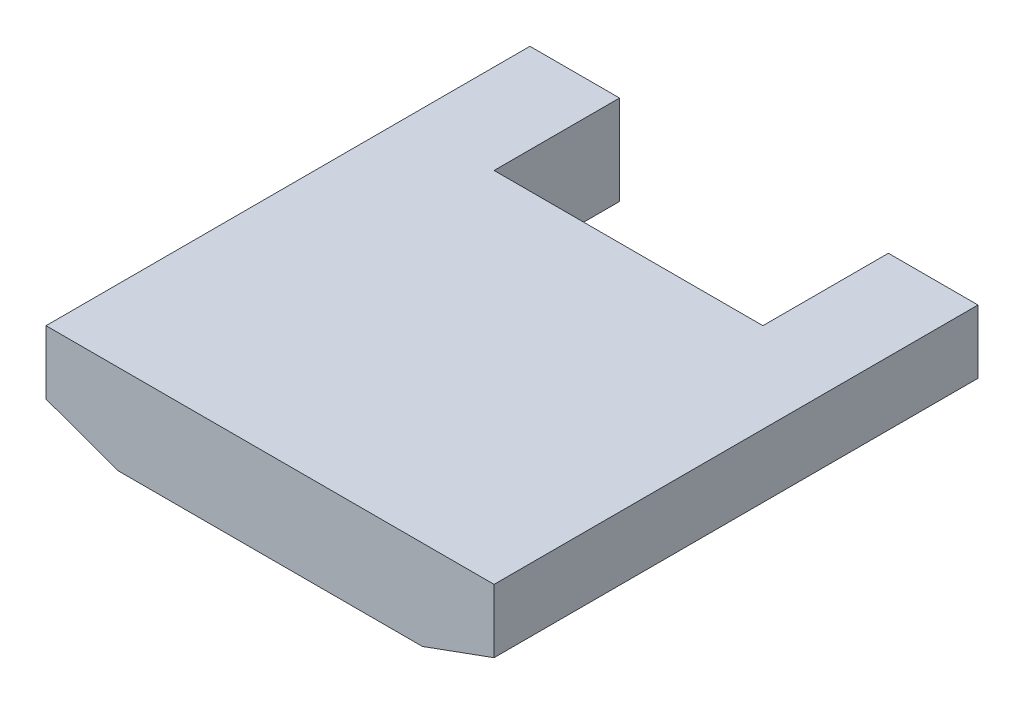
SolidWorks part; units mm, degrees
ref_plane "Front Plane" through (0, 0, 0) normal (0, 0, 1) x (1, 0, 0)
ref_plane "Top Plane" through (0, 0, 0) normal (0, 1, 0) x (1, 0, 0)
ref_plane "Right Plane" through (0, 0, 0) normal (1, 0, 0) x (0, 0, -1)
sketch "Sketch1" plane through (0, 0, 0) normal (0, 1, 0) x (1, 0, 0)
  line L0 (0, 0) -> (63.5, 0)
  line L1 (63.5, 0) -> (63.5, 68.58)
  line L2 (63.5, 68.58) -> (50.8, 68.58)
  line L3 (50.8, 68.58) -> (50.8, 50.8)
  line L4 (50.8, 50.8) -> (12.7, 50.8)
  line L5 (12.7, 50.8) -> (12.7, 68.58)
  line L6 (12.7, 68.58) -> (0, 68.58)
  line L7 (0, 68.58) -> (0, 0)
  dimension "D1" = 38.1
  dimension "D2" = 50.8
  dimension "D3" = 17.78
  dimension "D4" = 12.7
extrude "Boss-Extrude1" add sketch "Sketch1" along normal blind 12.7
chamfer "Chamfer1" distance 10.16 angle 20 2 edges at (0, 0, -34.29) (63.5, 0, -34.29)
